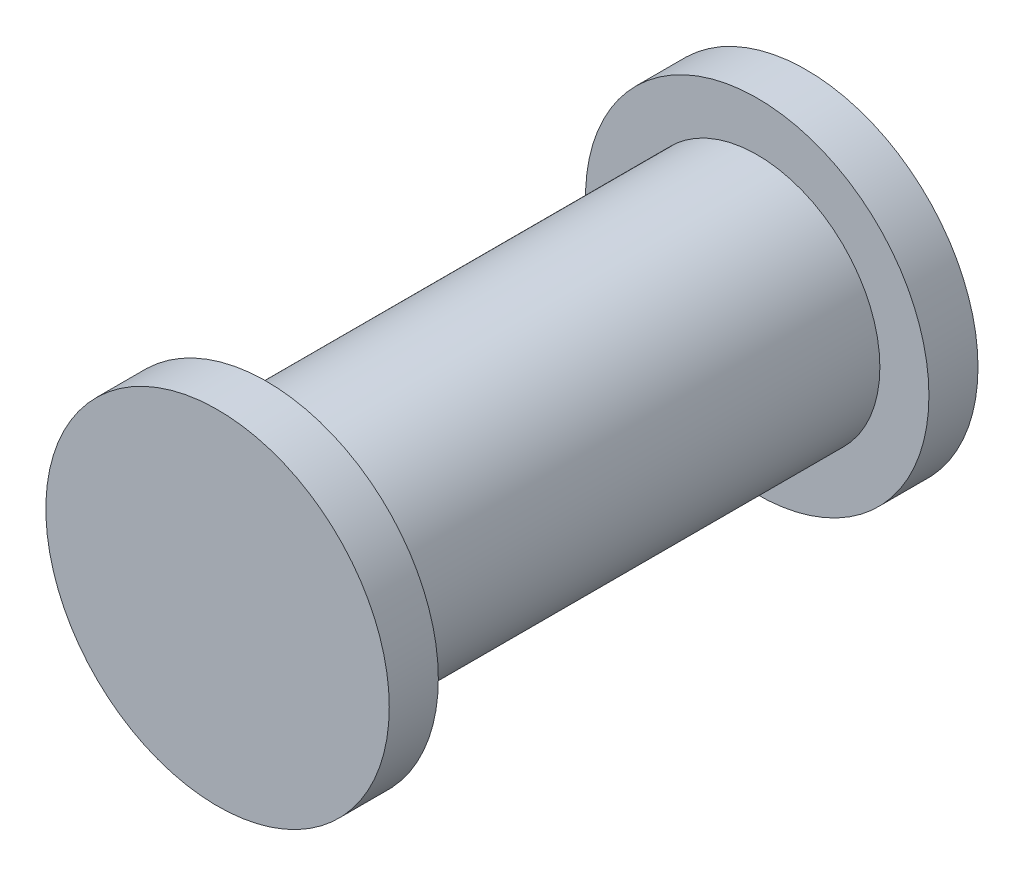
SolidWorks part; units mm, degrees
ref_plane "Front Plane" through (0, 0, 0) normal (0, 0, 1) x (1, 0, 0)
ref_plane "Top Plane" through (0, 0, 0) normal (0, 1, 0) x (1, 0, 0)
ref_plane "Right Plane" through (0, 0, 0) normal (1, 0, 0) x (0, 0, -1)
sketch "Sketch1" plane through (0, 0, 0) normal (0, 0, 1) x (1, 0, 0)
  circle A0 centre (0, 0) radius 25
  dimension "D1" = 50
extrude "Boss-Extrude1" add sketch "Sketch1" along normal blind 100
sketch "Sketch2" plane through (0, 0, 100) normal (0, 0, 1) x (1, 0, 0)
  circle A0 centre (0, 0) radius 35
  dimension "D1" = 70
extrude "Boss-Extrude2" add sketch "Sketch2" along normal blind 10
ref_plane "Plane1" through (0, 0, 50) normal (0, 0, -1) x (-1, 0, 0)
mirror "Mirror1" about plane through (0, 0, 50) normal (0, 0, -1) of "Boss-Extrude2"
